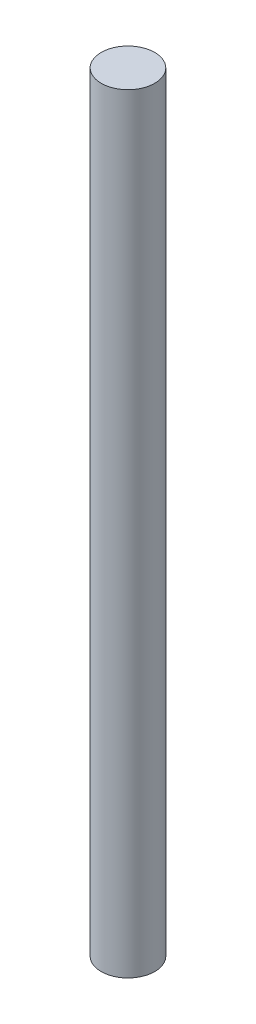
SolidWorks part; units mm, degrees
ref_plane "前视基准面" through (0, 0, 0) normal (0, 0, 1) x (1, 0, 0)
ref_plane "上视基准面" through (0, 0, 0) normal (0, 1, 0) x (1, 0, 0)
ref_plane "右视基准面" through (0, 0, 0) normal (1, 0, 0) x (0, 0, -1)
sketch "草图1" plane through (0, 0, 0) normal (0, 1, 0) x (1, 0, 0)
  circle A0 centre (0, 0) radius 8
  dimension "D1" = 16
extrude "凸台-拉伸1" add sketch "草图1" along normal blind 230
